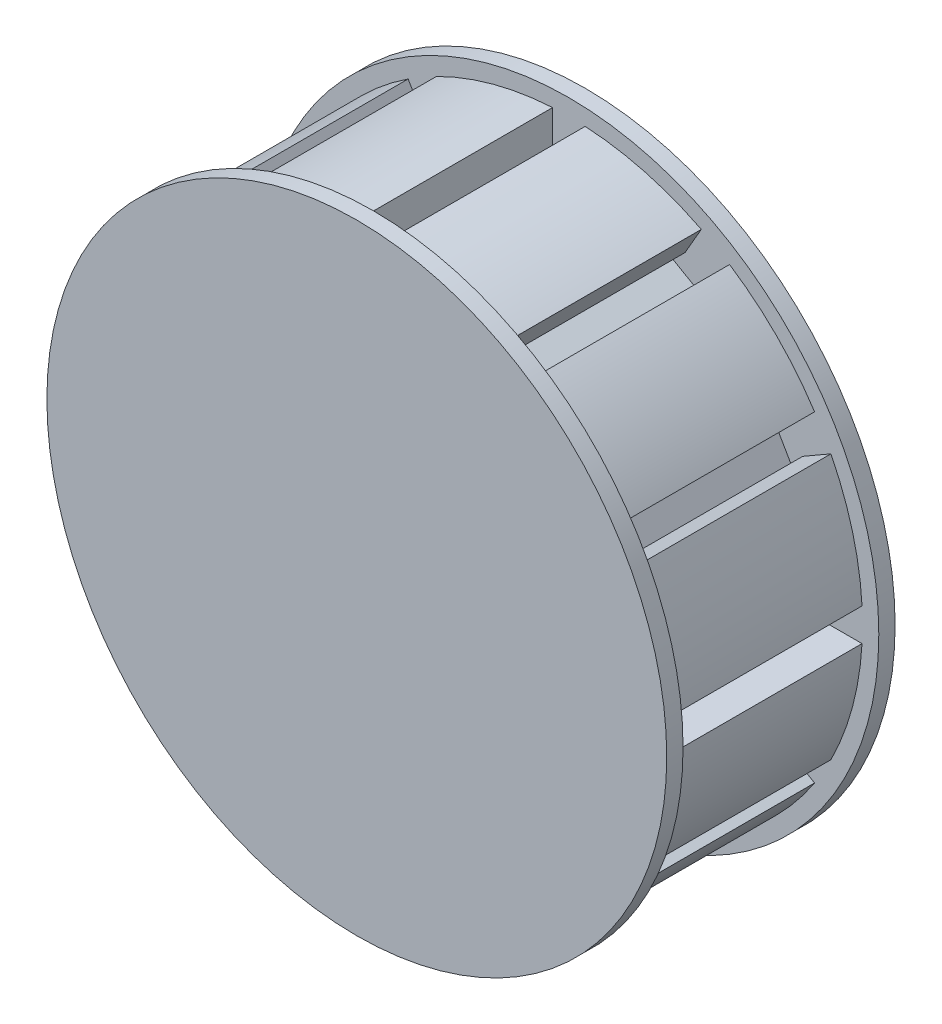
SolidWorks part; units mm, degrees
ref_plane "Front Plane" through (0, 0, 0) normal (0, 0, 1) x (1, 0, 0)
ref_plane "Top Plane" through (0, 0, 0) normal (0, 1, 0) x (1, 0, 0)
ref_plane "Right Plane" through (0, 0, 0) normal (1, 0, 0) x (0, 0, -1)
sketch "Sketch1" plane through (0, 0, 0) normal (0, 0, 1) x (1, 0, 0)
  circle A0 centre (0, 0) radius 28.575
  dimension "D1" = 57.15
extrude "Boss-Extrude1" add sketch "Sketch1" along normal mid plane 19.05
sketch "Sketch2" plane through (0, 0, 0) normal (0, 0, 1) x (1, 0, 0)
  line L0 (-1.5875, 28.5309) -> (-1.5875, 25.3559)
  line L1 (-1.5875, 25.3559) -> (-4.7625, 25.3559)
  line L2 (-4.7625, 25.3559) -> (-4.7625, 23.7684)
  line L3 (-4.7625, 23.7684) -> (4.7625, 23.7684)
  line L4 (4.7625, 23.7684) -> (4.7625, 25.3559)
  line L5 (4.7625, 25.3559) -> (1.5875, 25.3559)
  line L6 (1.5875, 25.3559) -> (1.5875, 28.5309)
  circle A0 centre (0, 0) radius 28.575 construction
  arc A1 (1.5875, 28.5309) -> (-1.5875, 28.5309) centre (0, 0) ccw
  point P8 (0, 0)
  point P11 (0, 23.7684)
  dimension "D1" = 9.525
  dimension "D2" = 3.175
  dimension "D3" = 3.175
  dimension "D4" = 1.5875
extrude "Cut-Extrude1" cut sketch "Sketch2" against normal mid plane 19.05
pattern_circular "CirPattern1" count 12 over 360 about axis through (0, 0, 0) along (0, 0, 1) of "Cut-Extrude1"
sketch "Sketch3" plane through (0, 0, -9.525) normal (0, 0, -1) x (-1, 0, 0)
  circle A0 centre (0, 0) radius 30.1625
  arc A1 (-25.5022, 12.8906) -> (-28.5309, 1.5875) centre (0, 0) ccw construction
  dimension "D1" = 1.5875
extrude "Boss-Extrude2" add sketch "Sketch3" along normal blind 1.5875
mirror "Mirror1" about plane through (0, 0, 0) normal (0, 0, 1) of "Boss-Extrude2"
